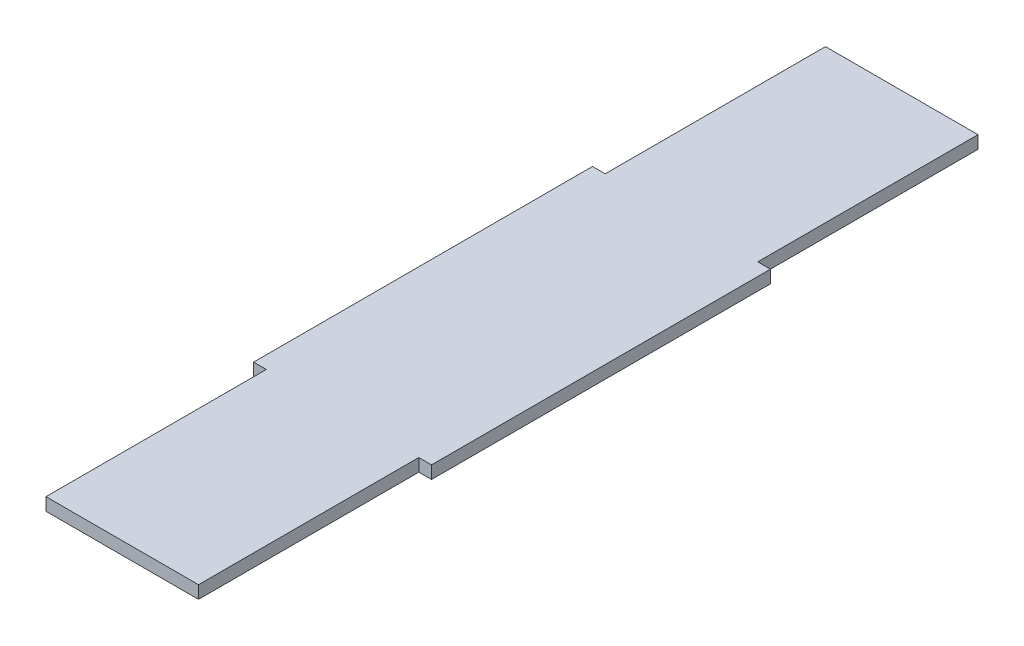
SolidWorks part; units mm, degrees
material "Thornel Mat VMA"
ref_plane "Front Plane" through (0, 0, 0) normal (0, 0, 1) x (1, 0, 0)
ref_plane "Top Plane" through (0, 0, 0) normal (0, 1, 0) x (1, 0, 0)
ref_plane "Right Plane" through (0, 0, 0) normal (1, 0, 0) x (0, 0, -1)
sketch "Sketch1" plane through (0, 0, 0) normal (0, 1, 0) x (1, 0, 0)
  line L0 (0, 0) -> (0, 92) construction
  line L1 (-18, -92) -> (18, -92)
  line L2 (-18, -92) -> (-18, 92)
  line L3 (-18, 92) -> (18, 92)
  line L4 (18, -92) -> (18, 92)
  line L5 (-18, -92) -> (18, 92) construction
  line L6 (-18, 92) -> (18, -92) construction
  line L7 (-21, -40) -> (-15, -40)
  line L8 (-21, -40) -> (-21, 40)
  line L9 (-21, 40) -> (-15, 40)
  line L10 (-15, -40) -> (-15, 40)
  line L11 (-21, -40) -> (-15, 40) construction
  line L12 (-21, 40) -> (-15, -40) construction
  line L13 (21, 40) -> (15, -40) construction
  line L14 (21, -40) -> (15, 40) construction
  line L15 (15, -40) -> (15, 40)
  line L16 (21, 40) -> (15, 40)
  line L17 (21, -40) -> (21, 40)
  line L18 (21, -40) -> (15, -40)
  point P0 (0, 0)
  point P6 (-18, 0)
  point P17 (18, 0)
  dimension "D1" = 184
  dimension "D2" = 36
  dimension "D3" = 6
  dimension "D4" = 80
extrude "Boss-Extrude1" add sketch "Sketch1" along normal blind 3 contours L4 L18 L15 L16 L3 L2 L9 L10 L7 L1 | L18 L4 L16 L15 | L18 L17 L16 L4 | L9 L8 L7 L2 | L7 L10 L9 L2
